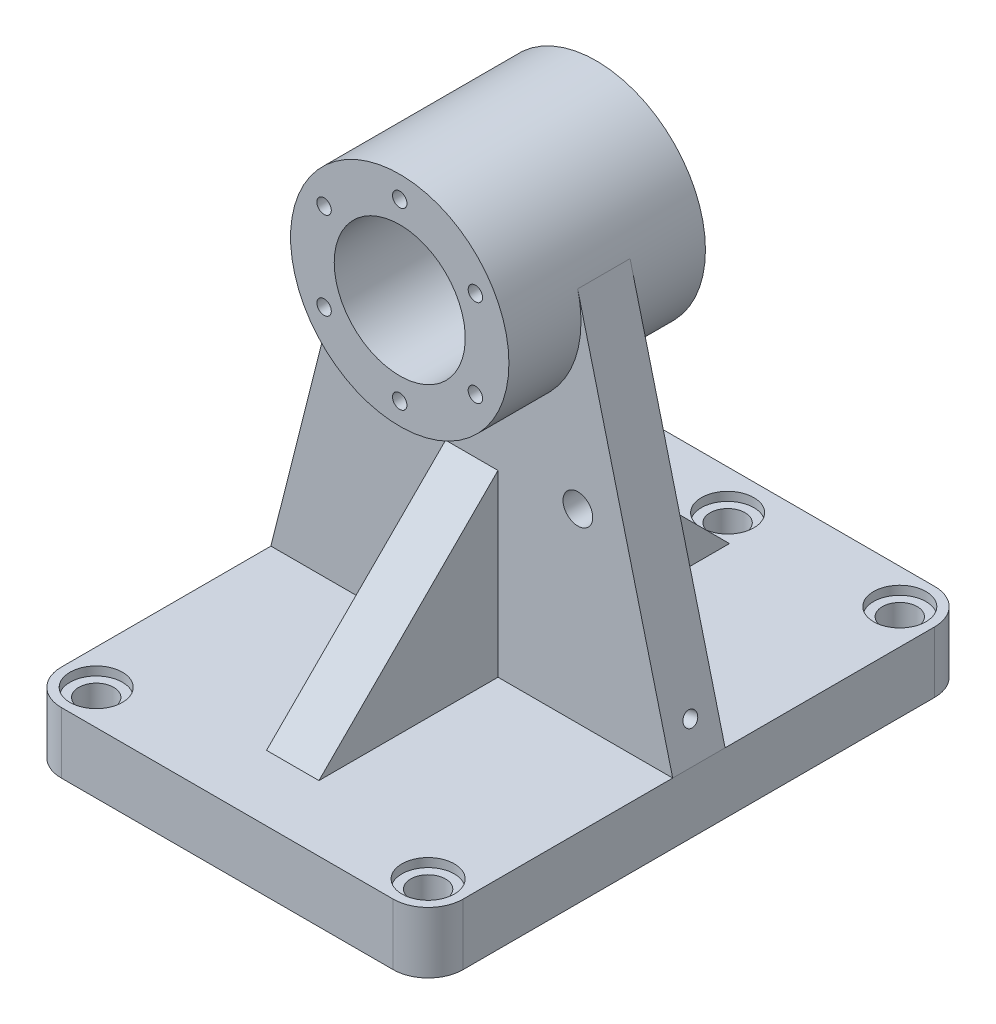
SolidWorks part; units mm, degrees
ref_plane "정면" through (0, 0, 0) normal (0, 0, 1) x (1, 0, 0)
ref_plane "윗면" through (0, 0, 0) normal (0, 1, 0) x (1, 0, 0)
ref_plane "우측면" through (0, 0, 0) normal (1, 0, 0) x (0, 0, -1)
sketch "스케치1" plane through (0, 0, 0) normal (0, 0, 1) x (1, 0, 0)
  circle A0 centre (0, 0) radius 15
  circle A1 centre (0, 0) radius 25
  dimension "D1" = 50
  dimension "D2" = 30
extrude "보스-돌출1" add sketch "스케치1" along normal mid plane 45
sketch "스케치2" plane through (0, 0, 0) normal (0, 0, 1) x (1, 0, 0)
  line L1 (-46, -80) -> (46, -80)
  line L2 (-46, -80) -> (-46, -94)
  line L3 (-46, -94) -> (46, -94)
  line L4 (46, -80) -> (46, -94)
  point P4 (0, -80)
  dimension "D1" = 92
  dimension "D2" = 14
  dimension "D3" = 80
extrude "보스-돌출2" add sketch "스케치2" along normal mid plane 124 separate body
sketch "스케치3" plane through (0, 0, 0) normal (0, 0, 1) x (1, 0, 0)
  line L0 (-24.2382, 6.1245) -> (-46, -80)
  line L1 (46, -80) -> (24.2382, 6.1245)
  line L2 (46, -80) -> (-46, -80)
  circle A0 centre (0, 0) radius 25 construction
  arc A1 (-24.2382, 6.1245) -> (24.2382, 6.1245) centre (0, 0) ccw
extrude "보스-돌출3" add sketch "스케치3" along normal mid plane 12 contours L1 A1 L0 L2
sketch "스케치4" plane through (0, 0, 0) normal (1, 0, 0) x (0, 0, -1)
  line L0 (-6, -39) -> (-47, -80)
  line L1 (-6, -80) -> (-6, 6.1245) construction
  line L2 (-62, -80) -> (-6, -80) construction
  line L3 (-62, -94) -> (-62, -80) construction
  dimension "D1" = 15
  dimension "D2" = 45
rib "보강대1" sketch "스케치4" sketch "스케치4" thickness 12 extrusion direction parallel to sketch draft on no parameters "D1"=12
mirror "대칭 복사1" about plane through (0, 0, 0) normal (0, 0, 1) of "보강대1"
fillet "필렛1" radius 8 4 edges at (-46, -87, -62) (46, -87, -62) (46, -87, 62) (-46, -87, 62)
hole_wizard "M1.6 소켓 머리 캡 나사용 카운터보어1" positions "3D스케치1" profile "스케치6" counterbore size "M1.6" standard "KS" end condition through all
sketch3d "3D스케치1"
  line L0 (-38, -94, 54) -> (-38, -80, 54) construction
  line L1 (38, -80, 54) -> (38, -94, 54) construction
  line L2 (38, -94, -54) -> (38, -80, -54) construction
  line L3 (-38, -80, -54) -> (-38, -94, -54) construction
  point P0 (-38, -80, 54)
  point P4 (38, -80, 54)
  point P8 (38, -80, -54)
  point P12 (-38, -80, -54)
sketch "스케치6" plane through (-38, -80, 54) normal (1, 0, 0) x (0, 0, 1)
  line L0 (0, 0) -> (0, 14)
  line L1 (0, 14) -> (4, 14)
  line L3 (4, 14) -> (4, 2)
  line L4 (4, 2) -> (6, 2)
  line L5 (6, 2) -> (6, 0)
  line L7 (6, 0) -> (0, 0)
  line L11 (0, -6.35) -> (0, 107.95) construction
  dimension "관통 구멍 지름" = 8
  dimension "관통 구멍 깊이" = 14
  dimension "카운터보어 지름" = 12
  dimension "카운터보어 깊이" = 2
hole_wizard "M6 나사 구멍1" positions "3D스케치2" profile "스케치9" tap size "M6" standard "KS" end condition through all
sketch3d "3D스케치2"
  point P0 (-22.9147, -34.421, 6)
sketch "스케치9" plane through (-22.9147, -34.421, 6) normal (1, 0, 0) x (0, -1, 0)
  line L0 (0, 0) -> (0, 68)
  line L1 (0, 68) -> (2.5, 68)
  line L2 (2.5, 68) -> (2.5, 0)
  line L5 (2.5, 0) -> (0, 0)
  line L11 (0, -6.35) -> (0, 107.95) construction
  dimension "관통 탭 드릴 지름" = 5
  dimension "관통 탭 드릴 깊이" = 68
cosmetic thread "구멍 나사산1" parameters "D2"=6
hole_wizard "M8 나사 구멍1" positions "3D스케치3" profile "스케치10" tap size "M8" standard "KS" end condition through all
sketch3d "3D스케치3"
  point P0 (24.2905, -37.484, 6)
sketch "스케치10" plane through (24.2905, -37.484, 6) normal (1, 0, 0) x (0, -1, 0)
  line L0 (0, 0) -> (0, 68)
  line L1 (0, 68) -> (3.4, 68)
  line L2 (3.4, 68) -> (3.4, 0)
  line L5 (3.4, 0) -> (0, 0)
  line L11 (0, -6.35) -> (0, 107.95) construction
  dimension "관통 탭 드릴 지름" = 6.8
  dimension "관통 탭 드릴 깊이" = 68
cosmetic thread "구멍 나사산2" parameters "D2"=8
hole_wizard "M1.6 소켓 머리 캡 나사용 카운터보어2" positions "3D스케치4" profile "스케치11" counterbore size "M1.6" standard "KS"
sketch3d "3D스케치4"
  point P0 (-0.3344, -80, -52.9114)
sketch "스케치11" plane through (-0.3344, -80, -52.9114) normal (1, 0, 0) x (0, 0, 1)
  line L0 (0, 0) -> (0, 14)
  line L1 (0, 14) -> (4, 14)
  line L3 (4, 14) -> (4, 2)
  line L4 (4, 2) -> (6, 2)
  line L5 (6, 2) -> (6, 0)
  line L7 (6, 0) -> (0, 0)
  line L11 (0, -6.35) -> (0, 107.95) construction
  dimension "관통 구멍 지름" = 8
  dimension "관통 구멍 깊이" = 14
  dimension "카운터보어 지름" = 12
  dimension "카운터보어 깊이" = 2
sketch "스케치13" plane through (0, 0, 22.5) normal (0, 0, 1) x (1, 0, 0)
  point P1 (0, 20)
  point P5 (0, 0)
  dimension "D1" = 20
hole_wizard "M4 나사 구멍1" positions "3D스케치5" profile "스케치15" tap size "M4" standard "KS"
sketch3d "3D스케치5"
  point P0 (0, 20, 22.5)
sketch "스케치15" plane through (0, 20, 22.5) normal (1, 0, 0) x (0, -1, 0)
  line L0 (0, 0) -> (0, 12.4914)
  line L1 (0, 12.4914) -> (1.65, 11.5)
  line L2 (1.65, 11.5) -> (1.65, 0)
  line L5 (1.65, 0) -> (0, 0)
  line L10 (0, 12.4914) -> (-1.65, 11.5) construction
  line L11 (0, -6.35) -> (0, 107.95) construction
  dimension "탭 드릴 지름" = 3.3
  dimension "탭 드릴 깊이" = 11.5
  dimension "드릴 각도" = 118
cosmetic thread "구멍 나사산3" parameters "D1"=8, "D2"=4
pattern_circular "원형 패턴1" count 6 over 360 about axis through (0, 0, 0) along (0, 0, 1) of "M4 나사 구멍1"
cosmetic thread "구멍 나사산4" parameters "D1"=8, "D2"=4
cosmetic thread "구멍 나사산5" parameters "D1"=8, "D2"=4
cosmetic thread "구멍 나사산6" parameters "D1"=8, "D2"=4
cosmetic thread "구멍 나사산7" parameters "D1"=8, "D2"=4
cosmetic thread "구멍 나사산8" parameters "D1"=8, "D2"=4
mirror "대칭 복사2" about plane through (0, 0, 0) normal (0, 0, 1) of "원형 패턴1", "M4 나사 구멍1"
cosmetic thread "구멍 나사산9" parameters "D1"=8, "D2"=4
cosmetic thread "구멍 나사산10" parameters "D1"=8, "D2"=4
cosmetic thread "구멍 나사산11" parameters "D1"=8, "D2"=4
cosmetic thread "구멍 나사산12" parameters "D1"=8, "D2"=4
cosmetic thread "구멍 나사산13" parameters "D1"=8, "D2"=4
cosmetic thread "구멍 나사산14" parameters "D1"=8, "D2"=4
sketch "스케치17" plane through (24.2382, 6.1245, 0) normal (0.9695, 0.245, 0) x (0, 0, -1)
  line L0 (-6, -88.8313) -> (6, -88.8313) construction
  point P0 (0, -88.8313)
  point P1 (0, -80.8313)
  point P4 (0, 0)
  point P5 (0, 0)
  dimension "D1" = 8
hole_wizard "M4 나사 구멍2" positions "3D스케치7" profile "스케치18" tap size "M4" standard "KS"
sketch3d "3D스케치7"
  point P0 (44.0402, -72.2438, 0)
sketch "스케치18" plane through (44.0402, -72.2438, 0) normal (0, 0, 1) x (-0.245, 0.9695, 0)
  line L0 (0, 0) -> (0, 12.4914)
  line L1 (0, 12.4914) -> (1.65, 11.5)
  line L2 (1.65, 11.5) -> (1.65, 0)
  line L5 (1.65, 0) -> (0, 0)
  line L10 (0, 12.4914) -> (-1.65, 11.5) construction
  line L11 (0, -6.35) -> (0, 107.95) construction
  dimension "탭 드릴 지름" = 3.3
  dimension "탭 드릴 깊이" = 11.5
  dimension "드릴 각도" = 118
cosmetic thread "구멍 나사산15" parameters "D1"=8, "D2"=4
